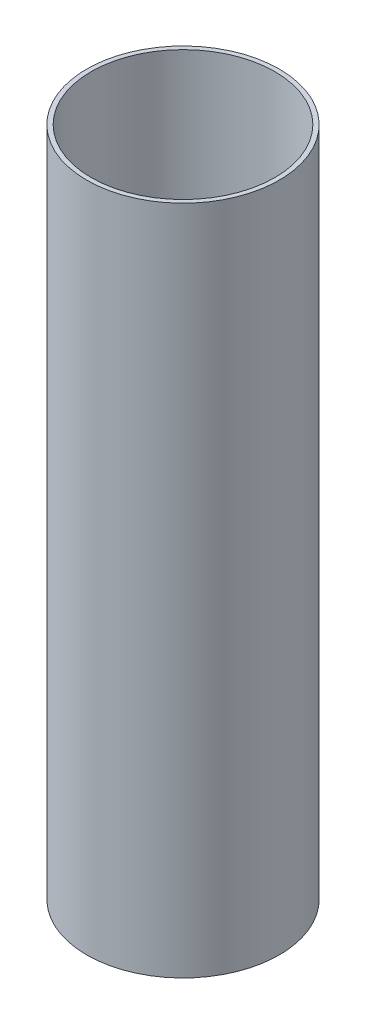
SolidWorks part; units mm, degrees
material "Kauczuk naturalny"
ref_plane "Płaszczyzna przednia" through (0, 0, 0) normal (0, 0, 1) x (1, 0, 0)
ref_plane "Płaszczyzna górna" through (0, 0, 0) normal (0, 1, 0) x (1, 0, 0)
ref_plane "Płaszczyzna prawa" through (0, 0, 0) normal (1, 0, 0) x (0, 0, -1)
sketch "Szkic1" plane through (0, 0, 0) normal (0, 0, 1) x (1, 0, 0)
  line L16 (0, 150) -> (0, -150) construction
  line L17 (0, 0) -> (62, 0) construction
  line L18 (62, 226.5) -> (65, 226.5)
  line L19 (62, 226.5) -> (62, -226.5)
  line L20 (62, -226.5) -> (65, -226.5)
  line L21 (65, 226.5) -> (65, -226.5)
  dimension "D1" = 65
  dimension "D2" = 3
  dimension "D3" = 453
revolve "Obrót1" add sketch "Szkic1" angle 360 about L16
